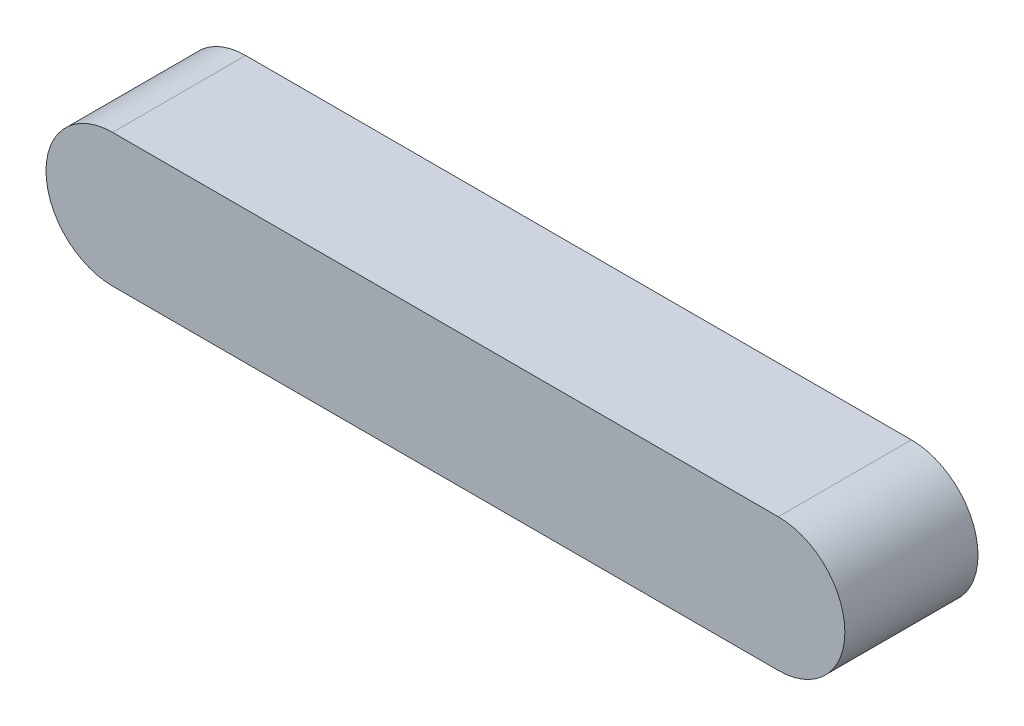
SolidWorks part; units mm, degrees
ref_plane "Front Plane" through (0, 0, 0) normal (0, 0, 1) x (1, 0, 0)
ref_plane "Top Plane" through (0, 0, 0) normal (0, 1, 0) x (1, 0, 0)
ref_plane "Right Plane" through (0, 0, 0) normal (1, 0, 0) x (0, 0, -1)
sketch "Sketch1" plane through (0, 0, 0) normal (0, 0, 1) x (1, 0, 0)
  line L0 (0, 0) -> (63.5, 0) construction
  line L1 (0, 6.35) -> (63.5, 6.35)
  line L2 (0, -6.35) -> (63.5, -6.35)
  arc A0 (0, 6.35) -> (0, -6.35) centre (0, 0) ccw
  arc A1 (63.5, -6.35) -> (63.5, 6.35) centre (63.5, 0) ccw
  point P3 (31.75, 0)
  dimension "D1" = 6.35
  dimension "D2" = 63.5
extrude "Boss-Extrude1" add sketch "Sketch1" along normal blind 12.7
equation "\"LENGTH\" = 2.5"
equation "\"D2@Sketch1\"=\"LENGTH\""
